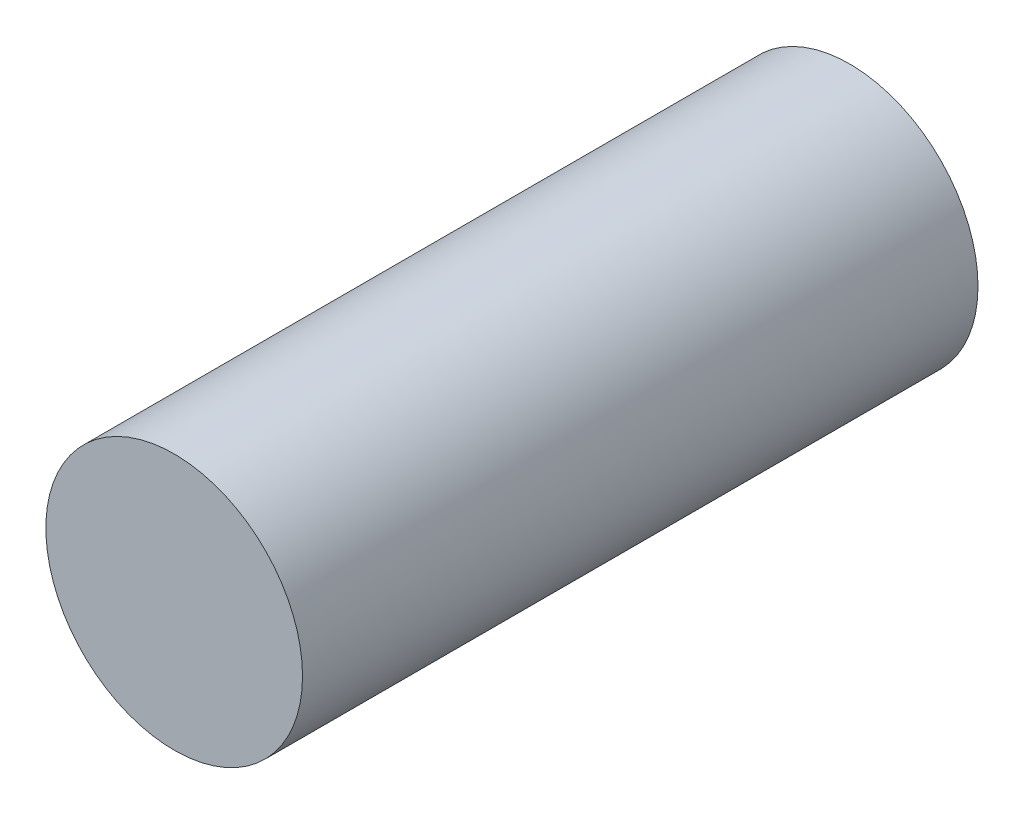
SolidWorks part; units mm, degrees
ref_plane "Front Plane" through (0, 0, 0) normal (0, 0, 1) x (1, 0, 0)
ref_plane "Top Plane" through (0, 0, 0) normal (0, 1, 0) x (1, 0, 0)
ref_plane "Right Plane" through (0, 0, 0) normal (1, 0, 0) x (0, 0, -1)
sketch "Sketch1" plane through (0, 0, 0) normal (0, 0, 1) x (1, 0, 0)
  circle A0 centre (0, 0) radius 1.9
extrude "Boss-Extrude1" add sketch "Sketch1" along normal blind 10 contours A0
